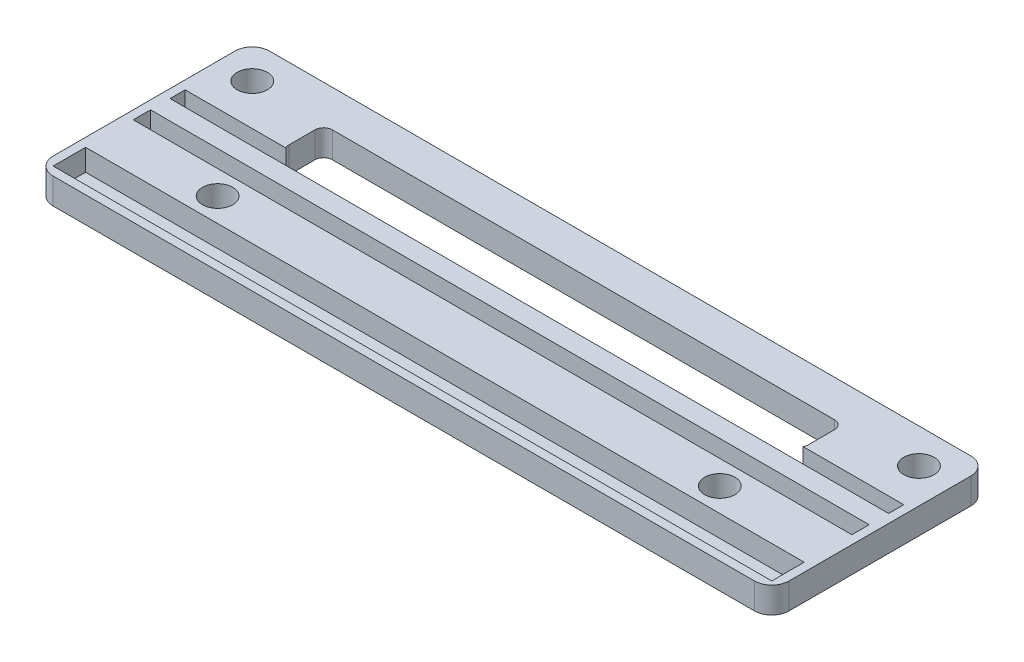
SolidWorks part; units mm, degrees
ref_plane "Front Plane" through (0, 0, 0) normal (0, 0, 1) x (1, 0, 0)
ref_plane "Top Plane" through (0, 0, 0) normal (0, 1, 0) x (1, 0, 0)
ref_plane "Right Plane" through (0, 0, 0) normal (1, 0, 0) x (0, 0, -1)
sketch "Sketch1" plane through (0, 0, 0) normal (0, 1, 0) x (1, 0, 0)
  line L0 (0, 12.5) -> (0, -12.5) construction
  line L1 (-42.5, 12.5) -> (42.5, 12.5)
  line L2 (-42.5, 12.5) -> (-42.5, -12.5)
  line L3 (-42.5, -12.5) -> (42.5, -12.5)
  line L4 (42.5, 12.5) -> (42.5, -12.5)
  dimension "D1" = 25
  dimension "D2" = 85
extrude "Boss-Extrude1" add sketch "Sketch1" along normal blind 3
sketch "Sketch2" plane through (0, 3, 0) normal (0, 1, 0) x (1, 0, 0)
  line L0 (0, -7.75) -> (0, -11.5) construction
  line L1 (-41.5, -7.75) -> (41.5, -7.75)
  line L2 (-41.5, -7.75) -> (-41.5, -11.5)
  line L3 (-41.5, -11.5) -> (41.5, -11.5)
  line L4 (41.5, -7.75) -> (41.5, -11.5)
  line L5 (0, 12.5) -> (0, -12.5) construction
  line L6 (42.5, 12.5) -> (-42.5, 12.5) construction
  line L7 (-42.5, -12.5) -> (42.5, -12.5) construction
  line L8 (42.5, -12.5) -> (42.5, 12.5) construction
  line L9 (0, -0.25) -> (0, -2.25) construction
  line L10 (-41.5, -0.25) -> (41.5, -0.25)
  line L11 (-41.5, -0.25) -> (-41.5, -2.25)
  line L12 (-41.5, -2.25) -> (41.5, -2.25)
  line L13 (41.5, -0.25) -> (41.5, -2.25)
  line L14 (-42.5, 12.5) -> (-42.5, -12.5) construction
  line L15 (0, 3.75) -> (0, 2) construction
  line L16 (-41.5, 3.75) -> (41.5, 3.75)
  line L17 (-41.5, 3.75) -> (-41.5, 2)
  line L18 (-41.5, 2) -> (41.5, 2)
  line L19 (41.5, 3.75) -> (41.5, 2)
  point P28 (0, 0)
  dimension "D1" = 3.75
  dimension "D2" = 1
  dimension "D3" = 1
  dimension "D4" = 2
  dimension "D5" = 5.5
  dimension "D6" = 1
  dimension "D7" = 1.75
  dimension "D8" = 2.25
extrude "Cut-Extrude1" cut sketch "Sketch2" against normal blind 2.5
sketch "Sketch3" plane through (0, 3, 0) normal (0, 1, 0) x (1, 0, 0)
  line L0 (-42.5, 12.5) -> (-42.5, -12.5) construction
  line L1 (42.5, 12.5) -> (-42.5, 12.5) construction
  line L2 (0, -12.5) -> (0, 12.5) construction
  line L3 (-42.5, -12.5) -> (42.5, -12.5) construction
  line L4 (-29, -2.25) -> (-29, -7.75) construction
  line L5 (-41.5, -2.25) -> (41.5, -2.25) construction
  line L6 (41.5, -7.75) -> (-41.5, -7.75) construction
  circle A0 centre (-38.5, 8.5) radius 1.75
  circle A1 centre (38.5, 8.5) radius 1.75
  circle A2 centre (-29, -5) radius 1.75
  circle A3 centre (29, -5) radius 1.75
  dimension "D1" = 3.5
  dimension "D4" = 3.5
  dimension "D2" = 4
  dimension "D3" = 4
  dimension "D5" = 29
extrude "Cut-Extrude2" cut sketch "Sketch3" against normal through all
sketch "Sketch4" plane through (0, 3, 0) normal (0, 1, 0) x (1, 0, 0)
  line L0 (0, 8.25) -> (0, 3.25) construction
  line L1 (-30, 8.25) -> (30, 8.25)
  line L2 (-30, 8.25) -> (-30, 3.25)
  line L3 (-30, 3.25) -> (30, 3.25)
  line L4 (30, 8.25) -> (30, 3.25)
  line L5 (41.5, 3.75) -> (-41.5, 3.75) construction
  dimension "D1" = 5
  dimension "D2" = 0.5
  dimension "D3" = 60
extrude "Cut-Extrude3" cut sketch "Sketch4" against normal through all
fillet "Fillet1" radius 1 4 edges at (30, 0.25, -3.25) (30, 1.5, -8.25) (-30, 1.5, -8.25) (-30, 0.25, -3.25)
fillet "Fillet2" radius 2 4 edges at (42.5, 1.5, -12.5) (42.5, 1.5, 12.5) (-42.5, 1.5, 12.5) (-42.5, 1.5, -12.5)
